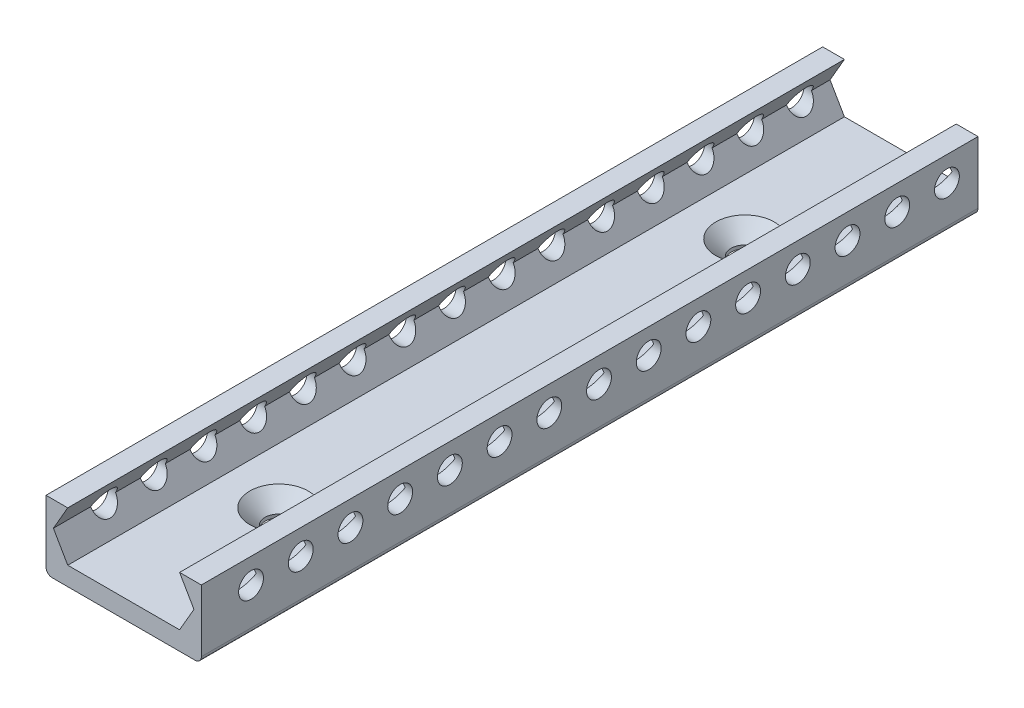
SolidWorks part; units mm, degrees
ref_plane "Front Plane" through (0, 0, 0) normal (0, 0, 1) x (1, 0, 0)
ref_plane "Top Plane" through (0, 0, 0) normal (0, 1, 0) x (1, 0, 0)
ref_plane "Right Plane" through (0, 0, 0) normal (1, 0, 0) x (0, 0, -1)
sketch "Sketch1" plane through (0, 0, 0) normal (0, 0, 1) x (1, 0, 0)
  line L0 (-9, 0) -> (9, 0)
  line L1 (-9, 0) -> (-11.3094, 4)
  line L2 (-11.3094, 4) -> (-9, 8)
  line L3 (-9, 8) -> (9, 8) construction
  line L4 (9, 8) -> (11.3094, 4)
  line L5 (11.3094, 4) -> (9, 0)
  line L6 (-9, 0) -> (-12.5, 0) construction
  line L8 (-12.5, 8) -> (-9, 8)
  line L9 (9, 8) -> (12.5, 8)
  line L10 (12.5, 8) -> (12.5, -3)
  line L11 (-12.5, 8) -> (-12.5, -3)
  line L12 (-12.5, -3) -> (12.5, -3)
  line L13 (-9, 0) -> (-11.3094, 0) construction
  line L14 (-11.3094, 0) -> (-11.3094, 4) construction
  line L15 (-11.3094, 8) -> (-9, 8) construction
  line L16 (-11.3094, 4) -> (-11.3094, 8) construction
  dimension "D1" = 18
  dimension "D2" = 120
  dimension "D3" = 120
  dimension "D4" = 120
  dimension "D5" = 120
  dimension "D6" = 8
  dimension "D7" = 3
  dimension "D8" = 3.5
extrude "Boss-Extrude1" add sketch "Sketch1" against normal blind 125
sketch "Sketch2" plane through (0, 0, 0) normal (0, 1, 0) x (1, 0, 0)
  line L0 (9, 125) -> (-9, 125) construction
  line L1 (9, 0) -> (-9, 0) construction
  line L2 (0, 124.6082) -> (0, -49875.3918) construction
  circle A0 centre (0, 100) radius 2
  circle A1 centre (0, 25) radius 2
  point P0 (0, 100)
  point P2 (0, 25)
  point P14 (0, 125)
  dimension "D1" = 4
  dimension "D2" = 25
  dimension "D3" = 25
sketch "Sketch3" plane through (12.5, 0, 0) normal (1, 0, 0) x (0, 0, -1)
  line L0 (125, 4) -> (0, 4) construction
  line L1 (0, -3) -> (0, 8) construction
  circle A0 centre (8, 4) radius 2
  dimension "D1" = 4
  dimension "D2" = 8
extrude "Cut-Extrude2" cut sketch "Sketch3" against normal blind 100
pattern_linear "LPattern1" count 28 spacing 8 along (0, 0, -1) of "Cut-Extrude2"
fillet "Fillet1" radius 1 2 edges at (12.5, -3, -62.5) (-12.5, -3, -62.5)
hole_wizard "CSK for M4 Flat Head Machine Screw1" positions "Sketch2" profile "Sketch4" countersink size "M4" standard "ANSI Metric" end condition through all
sketch "Sketch4" plane through (0, 0, -100) normal (1, 0, 0) x (0, 0, 1)
  line L0 (0, 0) -> (0, 3)
  line L1 (0, 3) -> (2.25, 3)
  line L2 (2.25, 3) -> (2.25, 2.45)
  line L3 (2.25, 2.45) -> (4.7, 0)
  line L5 (4.7, 0) -> (0, 0)
  line L6 (-2.25, 2.45) -> (-4.7, 0) construction
  line L11 (0, -6.35) -> (0, 107.95) construction
  dimension "Thru Hole Dia." = 4.5
  dimension "Thru Hole Depth" = 3
  dimension "Near C'Sink Dia." = 9.4
  dimension "Near C'Sink Angle" = 90
